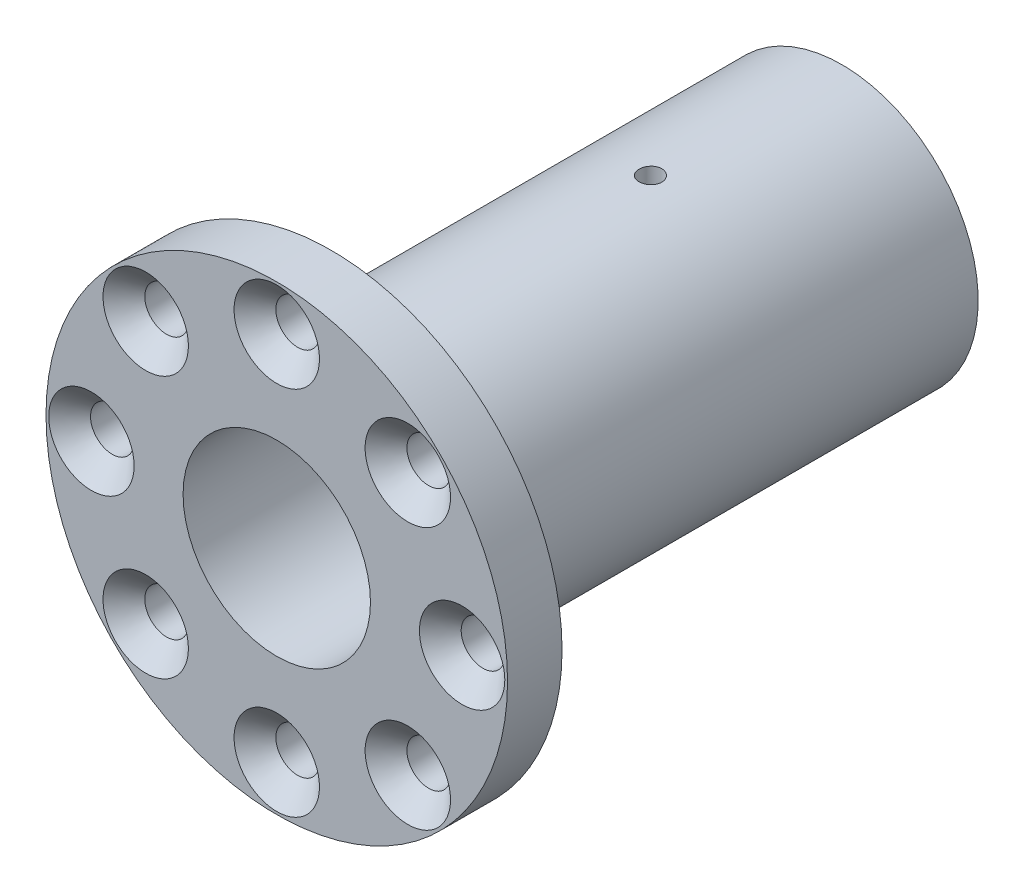
SolidWorks part; units mm, degrees
material "6061 Alloy"
ref_plane "Front" through (0, 0, 0) normal (0, 0, 1) x (1, 0, 0)
ref_plane "Top" through (0, 0, 0) normal (0, 1, 0) x (1, 0, 0)
ref_plane "Right" through (0, 0, 0) normal (1, 0, 0) x (0, 0, -1)
ref_plane "Plane1" through (0, 0, 0) normal (0, -1, 0) x (1, 0, 0)
sketch "Sketch1" plane through (0, 0, 0) normal (0, -1, 0) x (1, 0, 0)
  line L0 (25.4, 61.54) -> (0, 61.54)
  line L1 (0, 61.54) -> (0, 55.54)
  line L2 (0, 55.54) -> (25.4, 55.54)
  line L3 (25.4, 55.54) -> (25.4, 61.54)
  line L4 (0, 61.54) -> (0, 55.54) construction
revolve "Revolve1" add sketch "Sketch1" angle 360 about L4
sketch "Sketch2" plane through (0, 0, 55.54) normal (0, 0, -1) x (-1, 0, 0)
  circle A0 centre (0, 0) radius 15
extrude "Boss-Extrude1" add sketch "Sketch2" along normal blind 56.2
sketch "Sketch3" plane through (0, 0, -0.66) normal (0, 0, -1) x (-1, 0, 0)
  line L0 (2.5, 9.0585) -> (-2.5, 9.0585)
  line L1 (-2.5, 9.0585) -> (-2.5, 6.5495)
  line L2 (2.5, 6.5495) -> (2.5, 9.0585)
  arc A0 (-2.5, 6.5495) -> (2.5, 6.5495) centre (0, 0) cw
extrude "Cut-Extrude1" cut sketch "Sketch3" against normal blind 24.1
sketch "Sketch4" plane through (0, 0, 0) normal (0, 1, 0) x (1, 0, 0)
  line L0 (7.0104, 0.66) -> (0, 0.66)
  line L1 (0, 0.66) -> (0, -61.54)
  line L2 (0, -61.54) -> (10.3124, -61.54)
  line L3 (10.3124, -61.54) -> (10.3124, -23.44)
  line L4 (10.3124, -23.44) -> (7.0104, -23.44)
  line L5 (7.0104, -23.44) -> (7.0104, 0.66)
  line L6 (0, 0.66) -> (0, -61.54) construction
revolve "Cut-Revolve1" cut sketch "Sketch4" angle 360 about L6
hole_wizard "M3x0.5 Tapped Hole2" positions "Sketch6" profile "Sketch5" tap size "M3x0.5" standard "ANSI Metric"
sketch "Sketch6" plane through (0, 9.0585, 0) normal (0, -1, 0) x (-1, 0, 0)
  point P0 (0, -20.422)
sketch "Sketch5" plane through (0, 9.0585, 20.422) normal (1, 0, 0) x (0, 0, -1)
  line L0 (0, 0) -> (0, 16.3415)
  line L1 (0, 16.3415) -> (1.25, 16.3415)
  line L2 (1.25, 16.3415) -> (1.25, 0)
  line L5 (1.25, 0) -> (0, 0)
  line L11 (0, -6.35) -> (0, 107.95) construction
  dimension "Thru Tap Drill Dia." = 2.5
  dimension "Thru Tap Drill Depth" = 16.3415
hole_wizard "M3x0.5 Tapped Hole1" positions "Sketch8" profile "Sketch7" tap size "M3x0.5" standard "ANSI Metric"
sketch "Sketch8" plane through (0, 0, -0.66) normal (0, 0, -1) x (-1, 0, 0)
  point P0 (-11.5, 0)
  point P1 (-5.75, -9.9593)
  point P2 (5.75, -9.9593)
  point P3 (11.5, 0)
  point P4 (5.75, 9.9593)
  point P5 (-5.75, 9.9593)
sketch "Sketch7" plane through (11.5, 0, -0.66) normal (1, 0, 0) x (0, 1, 0)
  line L0 (0, 0) -> (0, 12.7511)
  line L1 (0, 12.7511) -> (1.25, 12)
  line L2 (1.25, 12) -> (1.25, 0)
  line L5 (1.25, 0) -> (0, 0)
  line L10 (0, 12.7511) -> (-1.25, 12) construction
  line L11 (0, -6.35) -> (0, 107.95) construction
  dimension "Tap Drill Dia." = 2.5
  dimension "Tap Drill Depth" = 12
  dimension "Drill Angle" = 118
hole_wizard "CSK for M4 Flat Head Machine Screw1" positions "Sketch10" profile "Sketch9" countersink size "M4" standard "ANSI Metric" end condition through all
sketch "Sketch10" plane through (0, 0, 61.54) normal (0, 0, 1) x (1, 0, 0)
  point P0 (0, 20.4)
  point P1 (14.425, 14.425)
  point P2 (20.4, 0)
  point P3 (14.425, -14.425)
  point P4 (0, -20.4)
  point P5 (-14.425, -14.425)
  point P6 (-20.4, 0)
  point P7 (-14.425, 14.425)
sketch "Sketch9" plane through (0, 20.4, 61.54) normal (1, 0, 0) x (0, -1, 0)
  line L0 (0, 0) -> (0, 62.2)
  line L1 (0, 62.2) -> (2.4, 62.2)
  line L2 (2.4, 62.2) -> (2.4, 2.3)
  line L3 (2.4, 2.3) -> (4.7, 0)
  line L5 (4.7, 0) -> (0, 0)
  line L6 (-2.4, 2.3) -> (-4.7, 0) construction
  line L11 (0, -6.35) -> (0, 107.95) construction
  dimension "Thru Hole Dia." = 4.8
  dimension "Thru Hole Depth" = 62.2
  dimension "Near C'Sink Dia." = 9.4
  dimension "Near C'Sink Angle" = 90
